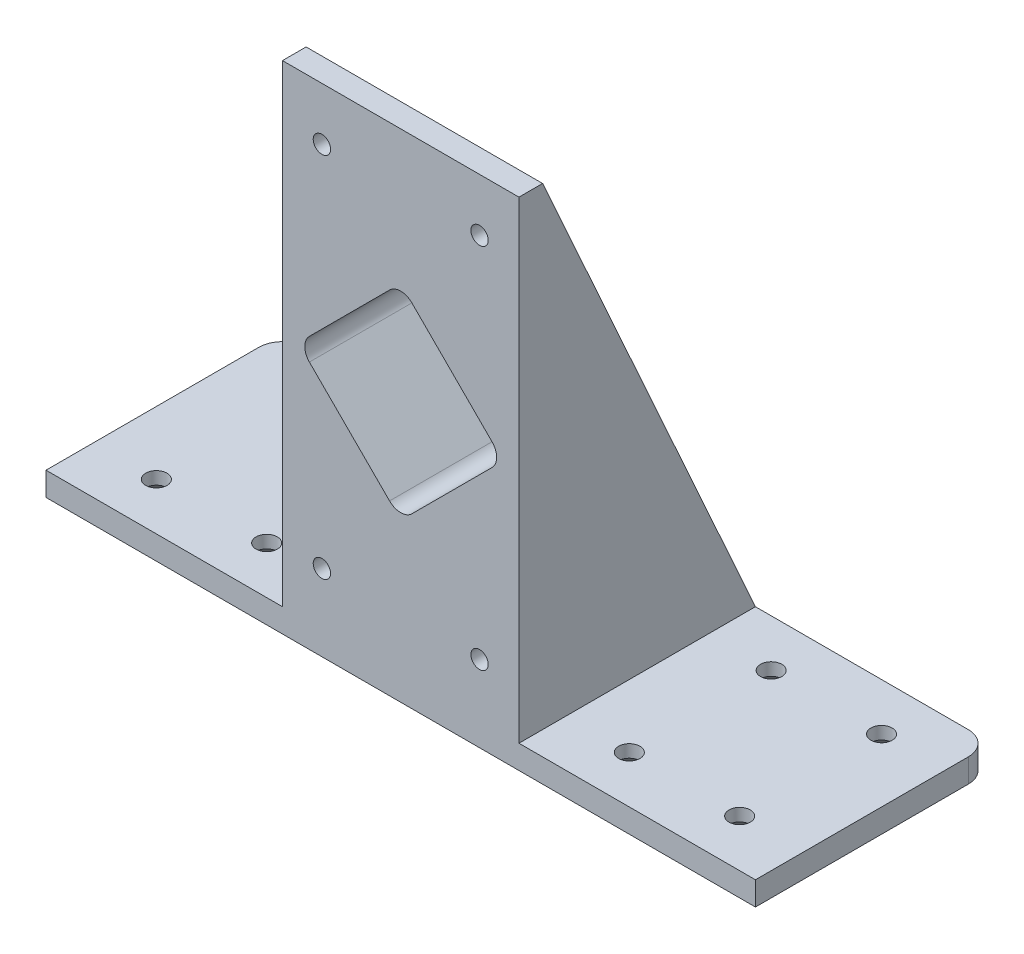
SolidWorks part; units mm, degrees
ref_plane "Front Plane" through (0, 0, 0) normal (0, 0, 1) x (1, 0, 0)
ref_plane "Top Plane" through (0, 0, 0) normal (0, 1, 0) x (1, 0, 0)
ref_plane "Right Plane" through (0, 0, 0) normal (1, 0, 0) x (0, 0, -1)
sketch "Sketch1" plane through (0, 0, 0) normal (0, 1, 0) x (1, 0, 0)
  line L1 (45, -15) -> (-45, -15)
  line L2 (45, -15) -> (45, 15)
  line L3 (45, 15) -> (-45, 15)
  line L4 (-45, -15) -> (-45, 15)
  line L5 (45, -15) -> (-45, 15) construction
  line L6 (45, 15) -> (-45, -15) construction
  point P0 (0, 0)
  dimension "D1" = 30
  dimension "D2" = 90
extrude "Boss-Extrude1" add sketch "Sketch1" along normal blind 3
sketch "Sketch3" plane through (0, 3, 0) normal (0, 1, 0) x (1, 0, 0)
  line L0 (-45, -15) -> (45, -15) construction
  line L1 (15, -12) -> (-15, -12)
  line L2 (15, -12) -> (15, -15)
  line L3 (15, -15) -> (-15, -15)
  line L4 (-15, -12) -> (-15, -15)
  line L5 (15, -12) -> (-15, -15) construction
  line L6 (15, -15) -> (-15, -12) construction
  line L7 (0, 15) -> (0, -15) construction
  line L8 (45, 15) -> (-45, 15) construction
  point P0 (0, -13.5)
  dimension "D1" = 3
  dimension "D2" = 30
extrude "Boss-Extrude2" add sketch "Sketch3" along normal blind 60
sketch "Sketch8" plane through (0, 0, 0) normal (1, 0, 0) x (0, 0, -1)
  line L0 (-12, 63) -> (15, 3)
rib "Rib5" sketch "Sketch8" sketch "Sketch8" thickness 30 extrusion direction parallel to sketch draft on no parameters "D1"=30
sketch "Sketch9" plane through (0, 0, 0) normal (0, -1, 0) x (1, 0, 0)
  line L0 (0, 15) -> (0, -15) construction
  line L1 (-45, 15) -> (45, 15) construction
  line L2 (45, -15) -> (-45, -15) construction
  line L3 (-45, 0) -> (45, 0) construction
  line L4 (-45, -15) -> (-45, 15) construction
  line L5 (45, 15) -> (45, -15) construction
  line L6 (-37, 9) -> (-23, 9) construction
  circle A1 centre (-37, 9) radius 1.35
  circle A2 centre (-23, 9) radius 1.35
  point P12 (-30, 9)
  point P13 (0, 0)
  dimension "D2" = 2.7
  dimension "D3" = 2.7
  dimension "D4" = 30
  dimension "D1" = 14
  dimension "D5" = 9
sketch "Sketch10" plane through (0, 0, 15) normal (0, 0, 1) x (1, 0, 0)
  line L0 (0, 63) -> (0, 0) construction
  line L1 (-15, 63) -> (15, 63) construction
  line L2 (-15, 33) -> (15, 33) construction
  line L3 (-15, 63) -> (-15, 3) construction
  line L4 (15, 63) -> (15, 3) construction
  circle A0 centre (-10, 56.3) radius 1.1
  circle A1 centre (10, 56.3) radius 1.1
  circle A2 centre (10, 9.7) radius 1.1
  circle A3 centre (-10, 9.7) radius 1.1
  dimension "D1" = 2.2
  dimension "D2" = 10
  dimension "D3" = 23.3
extrude "Cut-Extrude2" cut sketch "Sketch10" against normal up to next
ref_plane "Plane1" through (0, 0, -15) normal (0, 0, -1) x (-1, 0, 0)
sketch "Sketch12" plane through (0, 0, -15) normal (0, 0, -1) x (-1, 0, 0)
  line L0 (0, 63) -> (0, 0) construction
  line L1 (-15, 63) -> (15, 63) construction
  line L2 (-15, 33) -> (15, 33) construction
  line L3 (-15, 63) -> (-15, 3) construction
  line L4 (15, 63) -> (15, 3) construction
  circle A0 centre (-10, 56.3) radius 2.5
  circle A1 centre (10, 56.3) radius 2.5
  circle A2 centre (10, 9.7) radius 2.5
  circle A3 centre (-10, 9.7) radius 2.5
  dimension "D1" = 5
extrude "Cut-Extrude3" cut sketch "Sketch12" against normal offset from surface (27 mm away) 3 up to face at (-11.1, 9.7, 15)
fillet "Fillet1" radius 3 2 edges at (-45, 1.5, -15) (45, 1.5, -15)
sketch "Sketch13" plane through (0, 0, 15) normal (0, 0, 1) x (1, 0, 0)
  line L0 (0, 63) -> (0, 0) construction
  line L1 (-15, 63) -> (15, 63) construction
  line L2 (-15, 33) -> (15, 33) construction
  line L3 (-15, 63) -> (-15, 3) construction
  line L4 (15, 63) -> (15, 3) construction
  line L5 (0, 20) -> (-13, 33)
  line L6 (0, 20) -> (13, 33)
  line L7 (-13, 33) -> (0, 46)
  line L8 (13, 33) -> (0, 46)
  line L9 (0, 20) -> (0, 46) construction
  line L10 (-13, 33) -> (13, 33) construction
  point P11 (-10.1343, 26.1094)
  point P12 (0, 33)
  point P13 (0, 0)
  point P14 (0, 33)
  point P19 (-11.7444, 33)
  point P20 (0, 45.3356)
  dimension "D1" = 2
extrude "Cut-Extrude4" cut sketch "Sketch13" against normal up to next
fillet "Fillet2" radius 2 4 edges at (-13, 33, 6.75) (0, 46, 9.675) (13, 33, 6.75) (0, 20, 3.825)
hole_wizard "CSK for M2.5 Countersunk Flat Head Screw2" positions "3DSketch1" profile "Sketch14" countersink size "M2.5" standard "DIN" end condition up to next
sketch3d "3DSketch1"
  point P0 (-23, 0, 9)
  point P3 (-37, 0, 9)
sketch "Sketch14" plane through (-23, 0, 9) normal (1, 0, 0) x (0, 0, -1)
  line L0 (0, 0) -> (0, 3)
  line L1 (0, 3) -> (1.35, 3)
  line L2 (1.35, 3) -> (1.35, 1.4)
  line L3 (1.35, 1.4) -> (2.75, 0)
  line L5 (2.75, 0) -> (0, 0)
  line L6 (-1.35, 1.4) -> (-2.75, 0) construction
  line L11 (0, -6.35) -> (0, 107.95) construction
  dimension "Thru Hole Dia." = 2.7
  dimension "Thru Hole Depth" = 3
  dimension "Near C'Sink Dia." = 5.5
  dimension "Near C'Sink Angle" = 90
mirror "Mirror1" about plane through (0, 0, 0) normal (1, 0, 0) of "CSK for M2.5 Countersunk Flat Head Screw2" second plane through (0, 0, 0) second plane normal (0, 0, 1)
